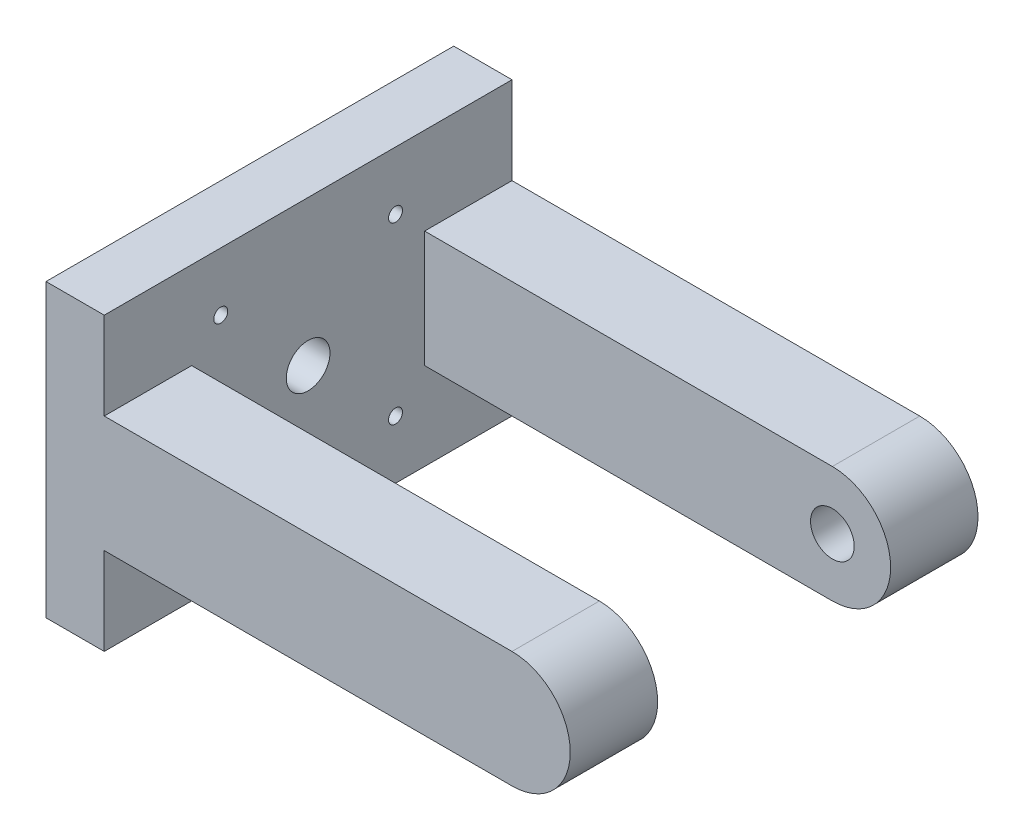
SolidWorks part; units mm, degrees
material "ABS"
ref_plane "Front Plane" through (0, 0, 0) normal (0, 0, 1) x (1, 0, 0)
ref_plane "Top Plane" through (0, 0, 0) normal (0, 1, 0) x (1, 0, 0)
ref_plane "Right Plane" through (0, 0, 0) normal (1, 0, 0) x (0, 0, -1)
sketch "Sketch1" plane through (0, 0, 0) normal (0, 0, 1) x (1, 0, 0)
  line L0 (-35, 10) -> (-35, 25)
  line L1 (-35, 10) -> (35, 10)
  line L3 (-35, -10) -> (35, -10)
  line L4 (-35, 25) -> (-45, 25)
  line L5 (-35, 10) -> (35, -10) construction
  line L6 (-35, -10) -> (35, 10) construction
  line L7 (-45, 25) -> (-45, -25)
  line L8 (-45, -25) -> (-35, -25)
  line L9 (-35, -25) -> (-35, -10)
  arc A0 (35, 10) -> (35, -10) centre (35, 0) cw
  point P0 (0, 0)
  dimension "D1" = 20
  dimension "D2" = 70
  dimension "D3" = 15
  dimension "D4" = 15
  dimension "D5" = 10
extrude "Boss-Extrude1" add sketch "Sketch1" against normal blind 70
sketch "Sketch2" plane through (0, 10, 0) normal (0, 1, 0) x (1, 0, 0)
  line L0 (-35, 0) -> (-35, 15) construction
  line L1 (-35, 70) -> (-35, 0) construction
  line L2 (-35, 70) -> (-35, 55) construction
  line L5 (-35, 15) -> (65.4957, 15)
  line L6 (-35, 15) -> (-35, 55)
  line L7 (-35, 55) -> (65.4957, 55)
  line L8 (65.4957, 15) -> (65.4957, 55)
  dimension "D1" = 15
  dimension "D2" = 15
extrude "Cut-Extrude1" cut sketch "Sketch2" against normal through all
sketch "Sketch3" plane through (0, 0, -55) normal (0, 0, 1) x (1, 0, 0)
  circle A0 centre (35, 0) radius 3.75
  dimension "D1" = 7.5
extrude "Cut-Extrude2" cut sketch "Sketch3" against normal blind 10
sketch "Sketch4" plane through (0, 0, -15) normal (0, 0, -1) x (-1, 0, 0)
  circle A0 centre (-33.8855, 0) radius 3.75
  dimension "D1" = 7.5
extrude "Cut-Extrude3" cut sketch "Sketch4" against normal blind 10
sketch "Sketch5" plane through (-35, 0, 0) normal (1, 0, 0) x (0, 0, -1)
  circle A0 centre (35, 0) radius 3.75
  dimension "D1" = 7.5
extrude "Cut-Extrude4" cut sketch "Sketch5" against normal through all
sketch "Sketch6" plane through (-45, 0, 0) normal (-1, 0, 0) x (0, 0, 1)
  line L1 (-50, 15) -> (-20, 15)
  line L2 (-50, 15) -> (-50, -15)
  line L3 (-50, -15) -> (-20, -15)
  line L4 (-20, 15) -> (-20, -15)
  line L5 (-50, 15) -> (-20, -15) construction
  line L6 (-50, -15) -> (-20, 15) construction
  point P0 (-35, 0)
  dimension "D1" = 30
  dimension "D2" = 30
hole_wizard "CSK for M2 Flat Head Machine Screw1" positions "Sketch7" profile "Sketch8" countersink size "M2" standard "ANSI Metric" end condition through all
sketch "Sketch7" plane through (-45, 0, 0) normal (-1, 0, 0) x (0, 0, 1)
  point P0 (-50, 15)
  point P3 (-20, 15)
  point P6 (-20, -15)
  point P9 (-50, -15)
sketch "Sketch8" plane through (-45, 15, -50) normal (0, 1, 0) x (0, 0, 1)
  line L0 (0, 0) -> (0, 90)
  line L1 (0, 90) -> (1.2, 90)
  line L2 (1.2, 90) -> (1.2, 1)
  line L3 (1.2, 1) -> (2.2, 0)
  line L5 (2.2, 0) -> (0, 0)
  line L6 (-1.2, 1) -> (-2.2, 0) construction
  line L11 (0, -6.35) -> (0, 107.95) construction
  dimension "Thru Hole Dia." = 2.4
  dimension "Thru Hole Depth" = 90
  dimension "Near C'Sink Dia." = 4.4
  dimension "Near C'Sink Angle" = 90
